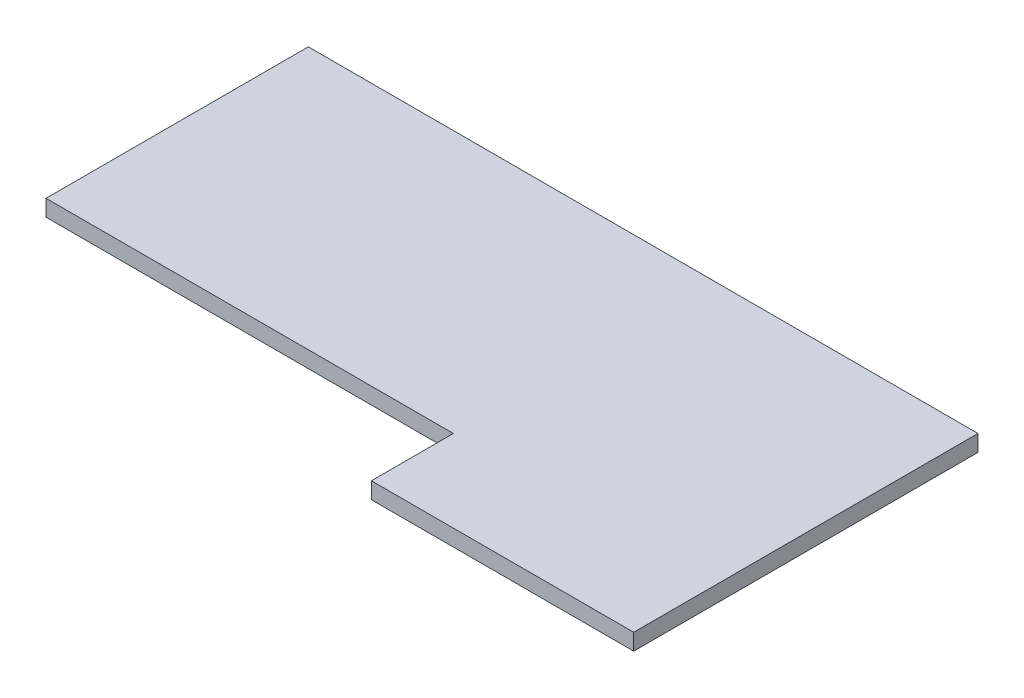
SolidWorks part; units mm, degrees
ref_plane "Front Plane" through (0, 0, 0) normal (0, 0, 1) x (1, 0, 0)
ref_plane "Top Plane" through (0, 0, 0) normal (0, 1, 0) x (1, 0, 0)
ref_plane "Right Plane" through (0, 0, 0) normal (1, 0, 0) x (0, 0, -1)
sketch "Sketch1" plane through (0, 0, 0) normal (0, 1, 0) x (1, 0, 0)
  line L0 (5.0993, 0.6846) -> (55.8993, 0.6846)
  line L1 (55.8993, 0.6846) -> (55.8993, -65.9904)
  line L2 (55.8993, -65.9904) -> (5.0993, -65.9904)
  line L3 (5.0993, -65.9904) -> (5.0993, -50.1154)
  line L4 (5.0993, -50.1154) -> (-73.7839, -50.1154)
  line L5 (-73.7839, -50.1154) -> (-73.7839, 0.6846)
  line L6 (-73.7839, 0.6846) -> (5.0993, 0.6846)
extrude "Boss-Extrude1" add sketch "Sketch1" along normal blind 3.175
